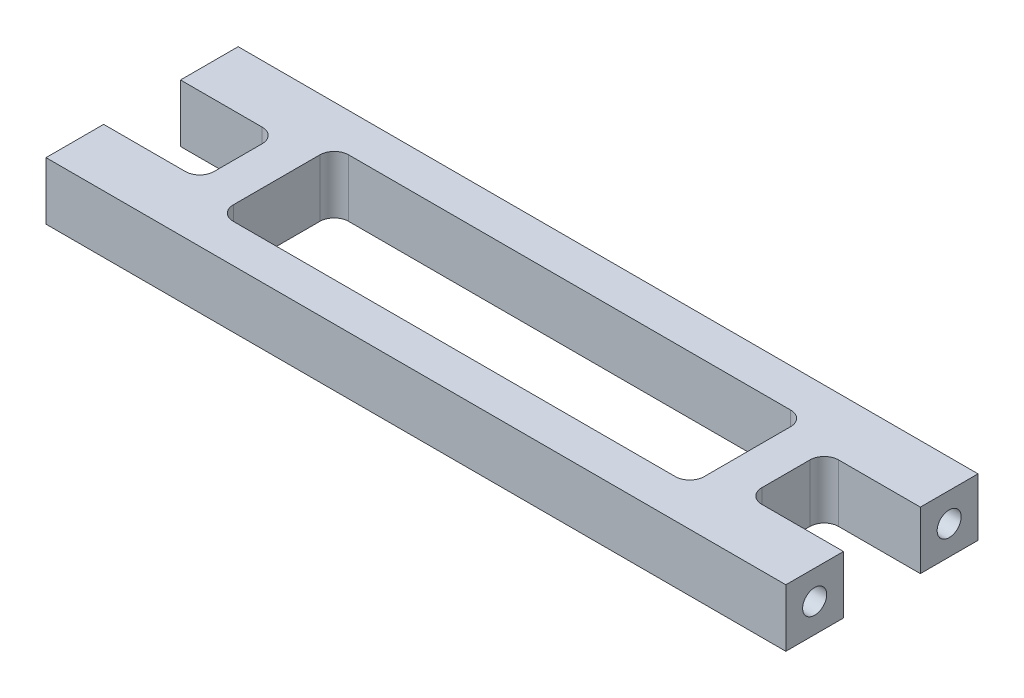
SolidWorks part; units mm, degrees
material "1060 Alloy"
ref_plane "Front Plane" through (0, 0, 0) normal (0, 0, 1) x (1, 0, 0)
ref_plane "Top Plane" through (0, 0, 0) normal (0, 1, 0) x (1, 0, 0)
ref_plane "Right Plane" through (0, 0, 0) normal (1, 0, 0) x (0, 0, -1)
sketch "Sketch1" plane through (0, 0, 0) normal (0, 1, 0) x (1, 0, 0)
  line L1 (0, 0) -> (77, 0)
  line L2 (0, 0) -> (0, 20)
  line L3 (0, 20) -> (77, 20)
  line L4 (77, 0) -> (77, 20)
  dimension "D1" = 20
  dimension "D2" = 77
extrude "Boss-Extrude1" add sketch "Sketch1" along normal blind 6
hole_wizard "Tap Drill for M3 Tap1" positions "Sketch4" profile "Sketch3" hole size "M3" standard "ISO"
sketch "Sketch4" plane through (0, 0, 0) normal (-1, 0, 0) x (0, 0, 1)
  line L0 (-20, 0) -> (0, 0) construction
  line L1 (-20, 6) -> (-20, 0) construction
  line L2 (0, 6) -> (0, 0) construction
  point P0 (-17, 3)
  point P2 (-3, 3)
  dimension "D1" = 3
  dimension "D2" = 3
  dimension "D3" = 3
sketch "Sketch3" plane through (0, 3, -17) normal (0, 1, 0) x (0, 0, 1)
  line L0 (0, 0) -> (0, 10.7511)
  line L1 (0, 10.7511) -> (1.25, 10)
  line L2 (1.25, 10) -> (1.25, 0)
  line L5 (1.25, 0) -> (0, 0)
  line L10 (0, 10.7511) -> (-1.25, 10) construction
  line L11 (0, -6.35) -> (0, 107.95) construction
  dimension "Hole Dia." = 2.5
  dimension "Hole Depth" = 10
  dimension "Drill Angle" = 118
hole_wizard "Tap Drill for M3 Tap2" positions "Sketch6" profile "Sketch5" hole size "M3" standard "ISO"
sketch "Sketch6" plane through (77, 0, 0) normal (1, 0, 0) x (0, 0, -1)
  line L0 (0, 0) -> (20, 0) construction
  line L1 (0, 6) -> (0, 0) construction
  line L2 (20, 6) -> (20, 0) construction
  point P0 (3, 3)
  point P2 (17, 3)
  dimension "D1" = 3
  dimension "D2" = 3
  dimension "D3" = 3
sketch "Sketch5" plane through (77, 3, -3) normal (0, 1, 0) x (0, 0, -1)
  line L0 (0, 0) -> (0, 10.7511)
  line L1 (0, 10.7511) -> (1.25, 10)
  line L2 (1.25, 10) -> (1.25, 0)
  line L5 (1.25, 0) -> (0, 0)
  line L10 (0, 10.7511) -> (-1.25, 10) construction
  line L11 (0, -6.35) -> (0, 107.95) construction
  dimension "Hole Dia." = 2.5
  dimension "Hole Depth" = 10
  dimension "Drill Angle" = 118
sketch "Sketch7" plane through (0, 6, 0) normal (0, 1, 0) x (1, 0, 0)
  line L1 (0, 20) -> (0, 0) construction
  line L3 (0, 14) -> (10, 14)
  line L8 (0, 14) -> (0, 6)
  line L9 (0, 6) -> (10, 6)
  line L10 (10, 14) -> (10, 6)
  line L12 (77, 0) -> (77, 20) construction
  line L13 (14, 16) -> (63, 16)
  line L14 (14, 16) -> (14, 4)
  line L16 (14, 4) -> (63, 4)
  line L17 (63, 16) -> (63, 4)
  line L18 (77, 14) -> (67, 14)
  line L19 (77, 14) -> (77, 6)
  line L20 (77, 6) -> (67, 6)
  line L21 (67, 14) -> (67, 6)
  line L22 (77, 20) -> (0, 20) construction
  line L23 (0, 0) -> (77, 0) construction
  dimension "D1" = 6
  dimension "D2" = 6
  dimension "D3" = 10
  dimension "D4" = 4
  dimension "D5" = 4
  dimension "D6" = 4
  dimension "D7" = 4
extrude "Cut-Extrude1" cut sketch "Sketch7" against normal up to next
fillet "Fillet1" radius 1.5 8 edges at (67, 3, -6) (67, 3, -14) (63, 3, -4) (14, 3, -4) (10, 3, -6) (10, 3, -14) (63, 3, -16) (14, 3, -16)
